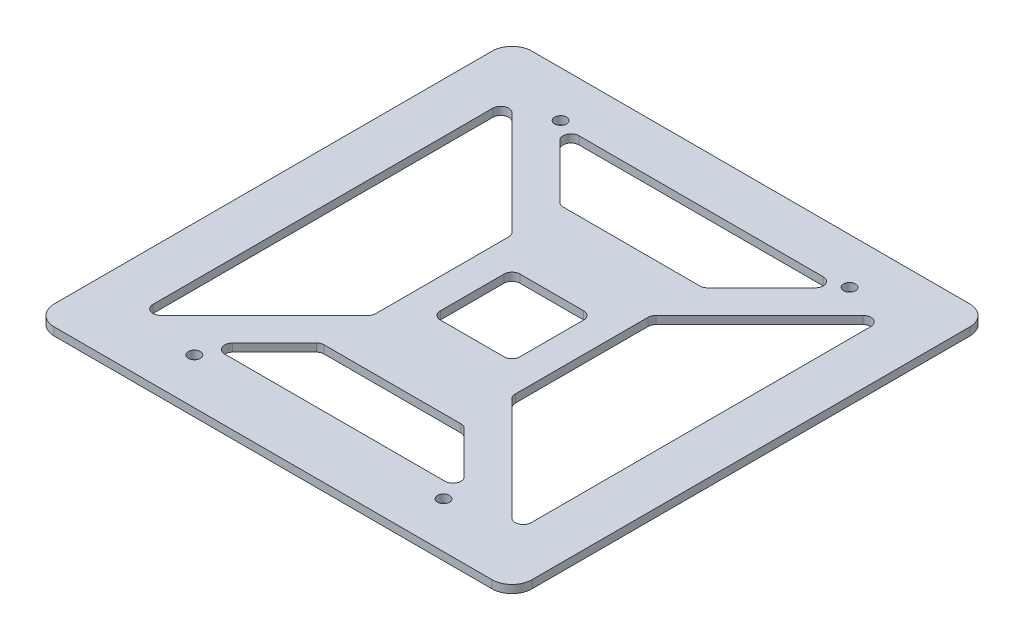
SolidWorks part; units mm, degrees
ref_plane "Front Plane" through (0, 0, 0) normal (0, 0, 1) x (1, 0, 0)
ref_plane "Top Plane" through (0, 0, 0) normal (0, 1, 0) x (1, 0, 0)
ref_plane "Right Plane" through (0, 0, 0) normal (1, 0, 0) x (0, 0, -1)
sketch "Sketch1" plane through (0, 0, 0) normal (0, 1, 0) x (1, 0, 0)
  line L1 (-60, 60) -> (60, 60)
  line L2 (-60, 60) -> (-60, -60)
  line L3 (-60, -60) -> (60, -60)
  line L4 (60, 60) -> (60, -60)
  line L5 (-60, 60) -> (60, -60) construction
  line L6 (-60, -60) -> (60, 60) construction
  point P0 (0, 0)
  dimension "D1" = 120
  dimension "D2" = 120
extrude "Boss-Extrude1" add sketch "Sketch1" along normal blind 2
fillet "Fillet1" radius 5 1 edges at (60, 1, 60)
fillet "Fillet2" radius 5 1 edges at (-60, 1, 60)
fillet "Fillet3" radius 5 1 edges at (60, 1, -60)
fillet "Fillet4" radius 5 1 edges at (-60, 1, -60)
sketch "Sketch2" plane through (0, 2, 0) normal (0, 1, 0) x (1, 0, 0)
  line L0 (-30, -18) -> (-47.5, -35.5)
  line L1 (47.5, -47.5) -> (-47.5, -47.5)
  line L2 (47.5, -47.5) -> (47.5, 47.5)
  line L3 (47.5, 47.5) -> (-47.5, 47.5)
  line L4 (-47.5, -47.5) -> (-47.5, 47.5)
  line L5 (47.5, -47.5) -> (-47.5, 47.5) construction
  line L6 (47.5, 47.5) -> (-47.5, -47.5) construction
  line L7 (30, -30) -> (-30, -30)
  line L8 (30, -30) -> (30, 30)
  line L9 (30, 30) -> (-30, 30)
  line L10 (-30, -30) -> (-30, 30)
  line L11 (30, -30) -> (-30, 30) construction
  line L12 (30, 30) -> (-30, -30) construction
  line L13 (10, -10) -> (-10, -10)
  line L14 (10, -10) -> (10, 10)
  line L15 (10, 10) -> (-10, 10)
  line L16 (-10, -10) -> (-10, 10)
  line L17 (10, -10) -> (-10, 10) construction
  line L18 (10, 10) -> (-10, -10) construction
  line L19 (-18, -30) -> (-35.5, -47.5)
  line L20 (0, 0) -> (-41.0196, 0)
  line L21 (0, 0) -> (0, -28.4966)
  line L22 (30, -18) -> (47.5, -35.5)
  line L23 (18, -30) -> (35.5, -47.5)
  line L24 (30, 18) -> (47.5, 35.5)
  line L25 (18, 30) -> (35.5, 47.5)
  line L26 (-18, 30) -> (-35.5, 47.5)
  line L27 (-30, 18) -> (-47.5, 35.5)
  line L28 (-32.5, -44.5) -> (32.5, -44.5)
  line L29 (-17.5, 17.5) -> (-47.5, 47.5)
  line L30 (-17.5, -17.5) -> (17.5, -17.5)
  line L31 (-17.5, -17.5) -> (-17.5, 17.5)
  line L32 (-17.5, 17.5) -> (17.5, 17.5)
  line L33 (17.5, -17.5) -> (17.5, 17.5)
  line L34 (-17.5, -17.5) -> (17.5, 17.5) construction
  line L35 (-17.5, 17.5) -> (17.5, -17.5) construction
  line L36 (-17.5, -17.5) -> (-47.5, -47.5)
  line L37 (17.5, 17.5) -> (47.5, 47.5)
  line L38 (17.5, -17.5) -> (17.5, 17.5)
  line L39 (17.5, -17.5) -> (47.5, -47.5)
  point P0 (0, 0)
  point P6 (0, 0)
  point P11 (0, 0)
  point P37 (0, 0)
  dimension "D1" = 20
  dimension "D2" = 20
  dimension "D3" = 95
  dimension "D4" = 60
  dimension "D5" = 135
  dimension "D6" = 12
  dimension "D7" = 135
  dimension "D8" = 12
  dimension "D9" = 65
  dimension "D10" = 35
  dimension "D11" = 35
  dimension "D12" = 0
extrude "Cut-Extrude1" cut sketch "Sketch2" against normal blind 10
fillet "Fillet5" radius 2 2 edges at (35.5, 1, -47.5) (-35.5, 1, -47.5)
fillet "Fillet6" radius 2 18 edges at (10, 1, -10) (10, 1, 10) (-10, 1, 10) (-10, 1, -10) (-32.5, 1, 44.5) (-18, 1, 30) (32.5, 1, 44.5) (18, 1, 30) (18, 1, -30) (-18, 1, -30) (47.5, 1, -47.5) (47.5, 1, 47.5) (17.5, 1, 17.5) (17.5, 1, -17.5) (-17.5, 1, -17.5) (-17.5, 1, 17.5) (-47.5, 1, 47.5) (-47.5, 1, -47.5)
sketch "Sketch4" plane through (0, 0, 0) normal (0, -1, 0) x (1, 0, 0)
  line L0 (0, 0) -> (0, -123.835)
  circle A0 centre (-36.293, -48.5) radius 1.5
  circle A1 centre (-31.293, 48.5) radius 1.5
  circle A2 centre (31.293, 48.5) radius 1.5
  circle A3 centre (36.293, -48.5) radius 1.5
extrude "Cut-Extrude2" cut sketch "Sketch4" against normal blind 10 contours A0 | A1 | A2 | A3
